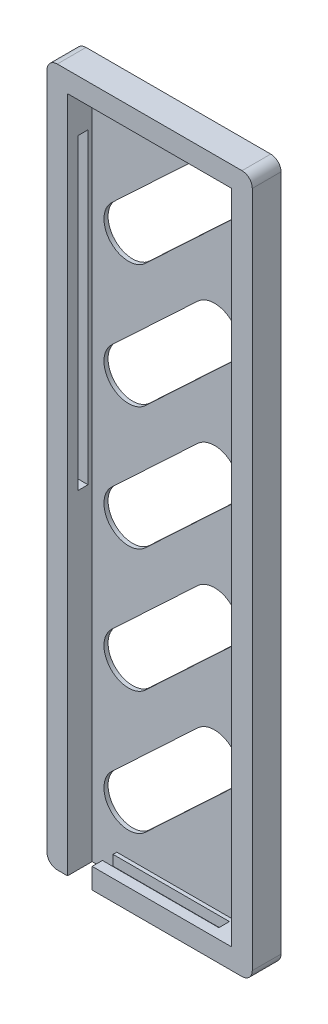
SolidWorks part; units mm, degrees
ref_plane "前视基准面" through (0, 0, 0) normal (0, 0, 1) x (1, 0, 0)
ref_plane "上视基准面" through (0, 0, 0) normal (0, 1, 0) x (1, 0, 0)
ref_plane "右视基准面" through (0, 0, 0) normal (1, 0, 0) x (0, 0, -1)
sketch "草图1" plane through (0, 0, 0) normal (0, 0, 1) x (1, 0, 0)
  line L1 (-1.8217, 18.8054) -> (8.1783, 18.8054)
  line L2 (-1.8217, 18.8054) -> (-1.8217, -15.1946)
  line L3 (-1.8217, -15.1946) -> (8.1783, -15.1946)
  line L4 (8.1783, 18.8054) -> (8.1783, -15.1946)
  dimension "D1" = 10
  dimension "D2" = 34
extrude "凸台-拉伸2" add sketch "草图1" along normal blind 1.4 contours L2 L1 L4 L3
sketch "草图2" plane through (0, 0, 1.4) normal (0, 0, 1) x (1, 0, 0)
  line L0 (-0.8217, 17.8054) -> (7.1783, 17.8054)
  line L1 (-0.8217, 17.8054) -> (-0.8217, -14.1946)
  line L2 (-0.8217, -14.1946) -> (7.1783, -14.1946)
  line L3 (7.1783, 17.8054) -> (7.1783, -14.1946)
  line L5 (-1.8217, 18.8054) -> (8.1783, 18.8054) construction
  line L6 (-1.8217, 18.8054) -> (-1.8217, -15.1946) construction
  dimension "D1" = 1
  dimension "D2" = 1
extrude "切除-拉伸1" cut sketch "草图2" against normal blind 1.2
sketch "草图4" plane through (0, 0, 1.4) normal (0, 0, 1) x (1, 0, 0)
  line L0 (-1.8217, -15.1946) -> (8.1783, -15.1946) construction
  line L1 (-0.8217, -14.1946) -> (0.3783, -14.1946)
  line L2 (-0.8217, -14.1946) -> (-0.8217, -15.1946)
  line L3 (-0.8217, -15.1946) -> (0.3783, -15.1946)
  line L4 (0.3783, -14.1946) -> (0.3783, -15.1946)
  dimension "D1" = 1.2
extrude "切除-拉伸4" cut sketch "草图4" against normal up to surface (1.2 mm away) up to face at (3.1783, 1.8054, 0.2)
fillet "圆角1" radius 0.5 1 edges at (-1.8217, -15.1946, 0.7)
fillet "圆角2" radius 0.5 3 edges at (-1.8217, 18.8054, 0.7) (8.1783, 18.8054, 0.7) (8.1783, -15.1946, 0.7)
sketch "草图6" plane through (0, 17.8054, 0) normal (0, -1, 0) x (1, 0, 0)
  line L1 (0.1783, 0.9) -> (6.1897, 0.9)
  line L2 (0.1783, 0.9) -> (0.1783, 0.3853)
  line L3 (0.1783, 0.3853) -> (6.1897, 0.3853)
  line L4 (6.1897, 0.9) -> (6.1897, 0.3853)
extrude "切除-拉伸6" cut sketch "草图6" against normal blind 0.5
sketch "草图7" plane through (-0.8217, 0, 0) normal (1, 0, 0) x (0, 0, -1)
  line L1 (-0.9, 15.7798) -> (-0.4016, 15.7798)
  line L2 (-0.9, 15.7798) -> (-0.9, 0.8071)
  line L3 (-0.9, 0.8071) -> (-0.4016, 0.8071)
  line L4 (-0.4016, 15.7798) -> (-0.4016, 0.8071)
extrude "切除-拉伸7" cut sketch "草图7" against normal blind 0.5
sketch "草图8" plane through (7.1783, 0, 0) normal (-1, 0, 0) x (0, 0, 1)
  line L1 (0.8904, 15.7748) -> (0.3927, 15.7748)
  line L2 (0.8904, 15.7748) -> (0.8904, -12.1291)
  line L3 (0.8904, -12.1291) -> (0.3927, -12.1291)
  line L4 (0.3927, 15.7748) -> (0.3927, -12.1291)
extrude "切除-拉伸8" cut sketch "草图8" against normal blind 0.5
sketch "草图10" plane through (0, -14.1946, 0) normal (0, 1, 0) x (1, 0, 0)
  line L0 (0.3783, -0.2) -> (0.3783, -1.4) construction
  line L1 (6.0494, -0.9) -> (0.3783, -0.9)
  line L2 (6.0494, -0.9) -> (6.0494, -0.3844)
  line L3 (6.0494, -0.3844) -> (0.3783, -0.3844)
  line L4 (0.3783, -0.9) -> (0.3783, -0.3844)
extrude "切除-拉伸9" cut sketch "草图10" against normal blind 0.5
sketch "草图11" plane through (0, 0, 0) normal (0, 0, -1) x (-1, 0, 0)
  line L0 (-5.139, 16.1463) -> (-0.9508, 12.214) construction
  line L1 (-4.3195, 17.0191) -> (-0.1313, 13.0867)
  line L2 (-5.9584, 15.2735) -> (-1.7703, 11.3412)
  line L3 (-5.9584, 9.2735) -> (-1.7703, 5.3412)
  line L4 (-4.3195, 11.0191) -> (-0.1313, 7.0867)
  line L5 (-5.139, 10.1463) -> (-0.9508, 6.214) construction
  line L6 (-5.9584, 3.2735) -> (-1.7703, -0.6588)
  line L7 (-4.3195, 5.0191) -> (-0.1313, 1.0867)
  line L8 (-5.139, 4.1463) -> (-0.9508, 0.214) construction
  line L9 (-5.9584, -2.7265) -> (-1.7703, -6.6588)
  line L10 (-4.3195, -0.9809) -> (-0.1313, -4.9133)
  line L11 (-5.139, -1.8537) -> (-0.9508, -5.786) construction
  line L12 (-5.9584, -8.7265) -> (-1.7703, -12.6588)
  line L13 (-4.3195, -6.9809) -> (-0.1313, -10.9133)
  line L14 (-5.139, -7.8537) -> (-0.9508, -11.786) construction
  arc A0 (-4.3195, 17.0191) -> (-5.9584, 15.2735) centre (-5.139, 16.1463) ccw
  arc A1 (-1.7703, 11.3412) -> (-0.1313, 13.0867) centre (-0.9508, 12.214) ccw
  arc A2 (-4.3195, 11.0191) -> (-5.9584, 9.2735) centre (-5.139, 10.1463) ccw
  arc A3 (-1.7703, 5.3412) -> (-0.1313, 7.0867) centre (-0.9508, 6.214) ccw
  arc A4 (-4.3195, 5.0191) -> (-5.9584, 3.2735) centre (-5.139, 4.1463) ccw
  arc A5 (-1.7703, -0.6588) -> (-0.1313, 1.0867) centre (-0.9508, 0.214) ccw
  arc A6 (-4.3195, -0.9809) -> (-5.9584, -2.7265) centre (-5.139, -1.8537) ccw
  arc A7 (-1.7703, -6.6588) -> (-0.1313, -4.9133) centre (-0.9508, -5.786) ccw
  arc A8 (-4.3195, -6.9809) -> (-5.9584, -8.7265) centre (-5.139, -7.8537) ccw
  arc A9 (-1.7703, -12.6588) -> (-0.1313, -10.9133) centre (-0.9508, -11.786) ccw
  point P2 (-3.0449, 14.1801)
  point P9 (-3.0449, 8.1801)
  point P16 (-3.0449, 2.1801)
  point P23 (-3.0449, -3.8199)
  point P30 (-3.0449, -9.8199)
extrude "切除-拉伸11" cut sketch "草图11" against normal up to next
